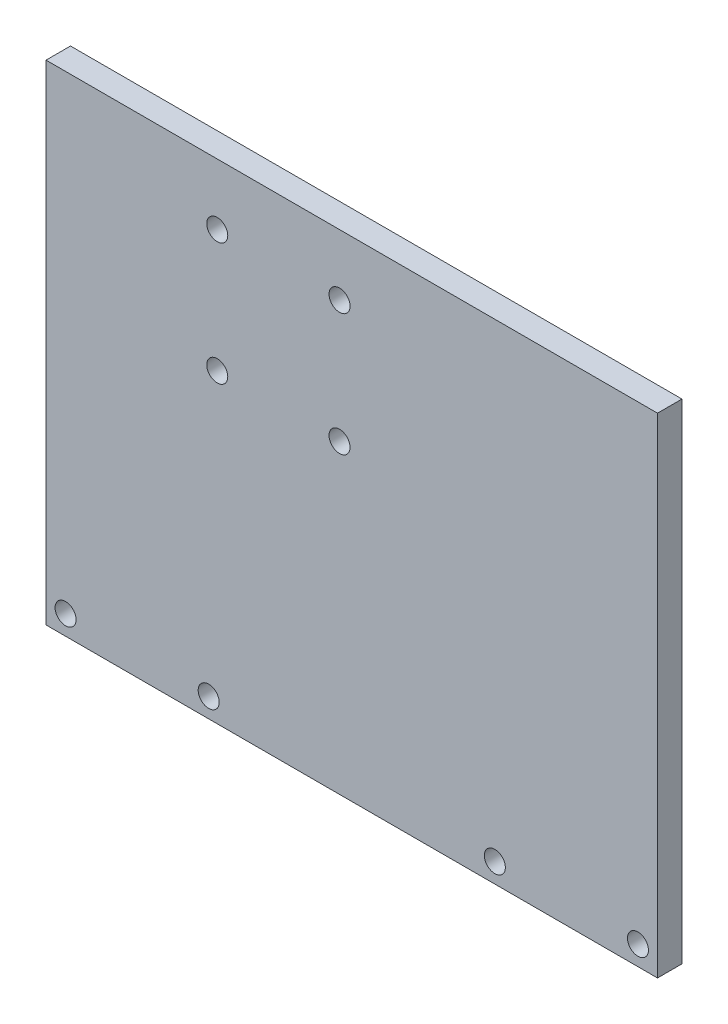
SolidWorks part; units mm, degrees
ref_plane "Front Plane" through (0, 0, 0) normal (0, 0, 1) x (1, 0, 0)
ref_plane "Top Plane" through (0, 0, 0) normal (0, 1, 0) x (1, 0, 0)
ref_plane "Right Plane" through (0, 0, 0) normal (1, 0, 0) x (0, 0, -1)
sketch "Sketch1" plane through (0, 0, 0) normal (0, 0, 1) x (1, 0, 0)
  line L0 (58.5, -46) -> (-58.5, -46) construction
  line L1 (-62.5, -50) -> (62.5, -50)
  line L2 (-62.5, -50) -> (-62.5, 50)
  line L3 (-62.5, 50) -> (62.5, 50)
  line L4 (62.5, -50) -> (62.5, 50)
  line L5 (-62.5, -50) -> (62.5, 50) construction
  line L6 (-62.5, 50) -> (62.5, -50) construction
  line L7 (-27.5, 12.5) -> (-2.5, 12.5) construction
  line L8 (-27.5, 12.5) -> (-27.5, 37.5) construction
  line L9 (-27.5, 37.5) -> (-2.5, 37.5) construction
  line L10 (-2.5, 12.5) -> (-2.5, 37.5) construction
  line L11 (-27.5, 12.5) -> (-2.5, 37.5) construction
  line L12 (-27.5, 37.5) -> (-2.5, 12.5) construction
  line L13 (62.5, -42) -> (-62.5, -42) construction
  line L14 (62.5, -42) -> (62.5, -50) construction
  line L15 (62.5, -50) -> (-62.5, -50) construction
  line L16 (-62.5, -42) -> (-62.5, -50) construction
  line L17 (62.5, -42) -> (-62.5, -50) construction
  line L18 (62.5, -50) -> (-62.5, -42) construction
  line L19 (29.25, -46) -> (-29.25, -46) construction
  line L20 (-58.5, -46) -> (-29.25, -46) construction
  line L21 (-29.25, -46) -> (0, -46) construction
  circle A0 centre (-27.5, 37.5) radius 2.15
  circle A1 centre (-2.5, 37.5) radius 2.15
  circle A2 centre (-2.5, 12.5) radius 2.15
  circle A3 centre (-27.5, 12.5) radius 2.15
  circle A4 centre (-58.5, -46) radius 4 construction
  circle A5 centre (-58.5, -46) radius 2.15
  circle A6 centre (58.5, -46) radius 2.15
  circle A7 centre (-29.25, -46) radius 2.15
  circle A8 centre (29.25, -46) radius 2.15
  point P0 (0, 0)
  point P6 (-15, 25)
  point P15 (0, -46)
  point P21 (0, -46)
  point P27 (0, -46)
  dimension "D3" = 4.3
  dimension "D1" = 125
  dimension "D2" = 100
  dimension "D4" = 25
  dimension "D5" = 65
  dimension "D6" = 75
  dimension "D7" = 8
extrude "Boss-Extrude1" add sketch "Sketch1" along normal mid plane 5
